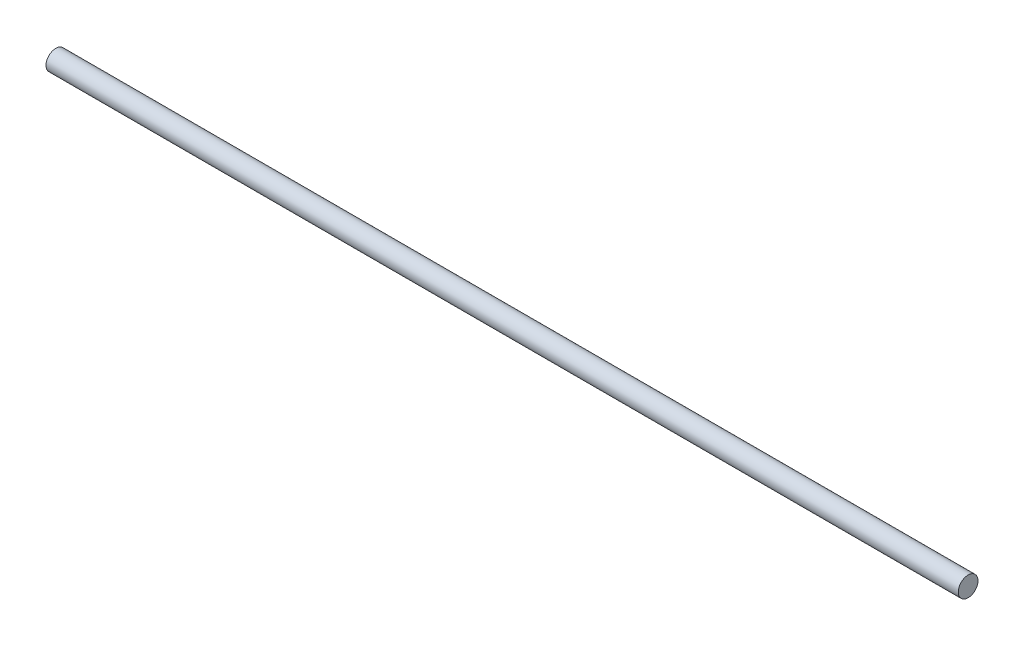
SolidWorks part; units mm, degrees
ref_plane "Alzado" through (0, 0, 0) normal (0, 0, 1) x (1, 0, 0)
ref_plane "Planta" through (0, 0, 0) normal (0, 1, 0) x (1, 0, 0)
ref_plane "Vista lateral" through (0, 0, 0) normal (1, 0, 0) x (0, 0, -1)
sketch "Croquis1" plane through (0, 0, 0) normal (1, 0, 0) x (0, 0, -1)
  circle A0 centre (0, 0) radius 4
  dimension "D1" = 8
extrude "Saliente-Extruir1" add sketch "Croquis1" along normal blind 370
